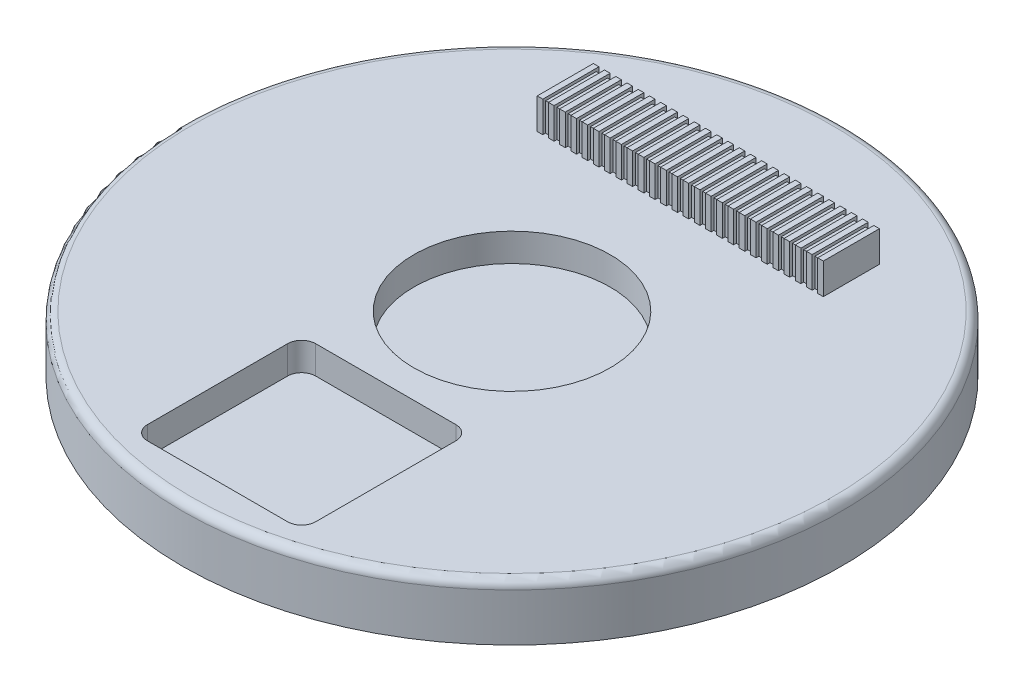
SolidWorks part; units mm, degrees
ref_plane "Front Plane" through (0, 0, 0) normal (0, 0, 1) x (1, 0, 0)
ref_plane "Top Plane" through (0, 0, 0) normal (0, 1, 0) x (1, 0, 0)
ref_plane "Right Plane" through (0, 0, 0) normal (1, 0, 0) x (0, 0, -1)
sketch "Sketch1" plane through (0, 0, 0) normal (0, 1, 0) x (1, 0, 0)
  circle A0 centre (0, 0) radius 117.5
  dimension "D1" = 235
extrude "Boss-Extrude1" add sketch "Sketch1" along normal blind 20
sketch "Sketch2" plane through (0, 20, 0) normal (0, 1, 0) x (1, 0, 0)
  line L1 (-25, -105) -> (25, -105)
  line L2 (-30, -100) -> (-30, -50)
  line L3 (-25, -45) -> (25, -45)
  line L4 (30, -100) -> (30, -50)
  line L5 (0, -45) -> (0, -105) construction
  line L6 (-30, -75) -> (30, -75) construction
  circle A0 centre (0, 0) radius 35
  arc A1 (25, -105) -> (30, -100) centre (25, -100) ccw
  arc A2 (-25, -105) -> (-30, -100) centre (-25, -100) cw
  arc A3 (25, -45) -> (30, -50) centre (25, -50) cw
  arc A4 (-30, -50) -> (-25, -45) centre (-25, -50) cw
  point P3 (0, -75)
  point P7 (0, 0)
  point P13 (-30, -105)
  point P18 (-30, -45)
  point P19 (0, 0)
  point P20 (0, 0)
  dimension "D1" = 70
  dimension "D3" = 5
  dimension "D2" = 60
  dimension "D4" = 75
extrude "Cut-Extrude1" cut sketch "Sketch2" against normal blind 10
sketch "Sketch3" plane through (0, 20, 0) normal (0, 1, 0) x (1, 0, 0)
  line L1 (-51, 80) -> (51, 80)
  line L2 (-51, 80) -> (-51, 60)
  line L3 (-51, 60) -> (51, 60)
  line L4 (51, 80) -> (51, 60)
  line L5 (0, 60) -> (0, 80) construction
  line L6 (-51, 70) -> (51, 70) construction
  point P0 (0, 70)
  point P4 (0, 0)
  point P5 (0, 0)
  dimension "D1" = 70
  dimension "D2" = 20
  dimension "D3" = 102
extrude "Boss-Extrude2" add sketch "Sketch3" along normal blind 10
sketch "Sketch6" plane through (0, 30, 0) normal (0, 1, 0) x (1, 0, 0)
  line L0 (-51, 70) -> (51, 70) construction
  line L1 (-51, 80) -> (-51, 60) construction
  line L2 (51, 60) -> (51, 80) construction
  line L3 (51, 80) -> (-51, 80) construction
  line L4 (-51, 60) -> (-49, 60)
  line L5 (-51, 60) -> (-51, 80)
  line L6 (-51, 80) -> (-49, 80)
  line L7 (-49, 60) -> (-49, 80)
  line L8 (-50, 80) -> (-50, 60) construction
  line L9 (-51, 70) -> (-49, 70) construction
  line L10 (-45, 60) -> (-45, 80)
  line L11 (-47, 60) -> (-45, 60)
  line L12 (-47, 60) -> (-47, 80)
  line L13 (-47, 80) -> (-45, 80)
  line L14 (-41, 60) -> (-41, 80)
  line L15 (-43, 60) -> (-41, 60)
  line L16 (-43, 60) -> (-43, 80)
  line L17 (-43, 80) -> (-41, 80)
  line L18 (-37, 60) -> (-37, 80)
  line L19 (-39, 60) -> (-37, 60)
  line L20 (-39, 60) -> (-39, 80)
  line L21 (-39, 80) -> (-37, 80)
  line L22 (-33, 60) -> (-33, 80)
  line L23 (-35, 60) -> (-33, 60)
  line L24 (-35, 60) -> (-35, 80)
  line L25 (-35, 80) -> (-33, 80)
  line L26 (-29, 60) -> (-29, 80)
  line L27 (-31, 60) -> (-29, 60)
  line L28 (-31, 60) -> (-31, 80)
  line L29 (-31, 80) -> (-29, 80)
  line L30 (-25, 60) -> (-25, 80)
  line L31 (-27, 60) -> (-25, 60)
  line L32 (-27, 60) -> (-27, 80)
  line L33 (-27, 80) -> (-25, 80)
  line L34 (-21, 60) -> (-21, 80)
  line L35 (-23, 60) -> (-21, 60)
  line L36 (-23, 60) -> (-23, 80)
  line L37 (-23, 80) -> (-21, 80)
  line L38 (-17, 60) -> (-17, 80)
  line L39 (-19, 60) -> (-17, 60)
  line L40 (-19, 60) -> (-19, 80)
  line L41 (-19, 80) -> (-17, 80)
  line L42 (-13, 60) -> (-13, 80)
  line L43 (-15, 60) -> (-13, 60)
  line L44 (-15, 60) -> (-15, 80)
  line L45 (-15, 80) -> (-13, 80)
  line L46 (-9, 60) -> (-9, 80)
  line L47 (-11, 60) -> (-9, 60)
  line L48 (-11, 60) -> (-11, 80)
  line L49 (-11, 80) -> (-9, 80)
  line L50 (-5, 60) -> (-5, 80)
  line L51 (-7, 60) -> (-5, 60)
  line L52 (-7, 60) -> (-7, 80)
  line L53 (-7, 80) -> (-5, 80)
  line L54 (-1, 60) -> (-1, 80)
  line L55 (-3, 60) -> (-1, 60)
  line L56 (-3, 60) -> (-3, 80)
  line L57 (-3, 80) -> (-1, 80)
  line L58 (3, 60) -> (3, 80)
  line L59 (1, 60) -> (3, 60)
  line L60 (1, 60) -> (1, 80)
  line L61 (1, 80) -> (3, 80)
  line L62 (7, 60) -> (7, 80)
  line L63 (5, 60) -> (7, 60)
  line L64 (5, 60) -> (5, 80)
  line L65 (5, 80) -> (7, 80)
  line L66 (11, 60) -> (11, 80)
  line L67 (9, 60) -> (11, 60)
  line L68 (9, 60) -> (9, 80)
  line L69 (9, 80) -> (11, 80)
  line L70 (15, 60) -> (15, 80)
  line L71 (13, 60) -> (15, 60)
  line L72 (13, 60) -> (13, 80)
  line L73 (13, 80) -> (15, 80)
  line L74 (19, 60) -> (19, 80)
  line L75 (17, 60) -> (19, 60)
  line L76 (17, 60) -> (17, 80)
  line L77 (17, 80) -> (19, 80)
  line L78 (23, 60) -> (23, 80)
  line L79 (21, 60) -> (23, 60)
  line L80 (21, 60) -> (21, 80)
  line L81 (21, 80) -> (23, 80)
  line L82 (27, 60) -> (27, 80)
  line L83 (25, 60) -> (27, 60)
  line L84 (25, 60) -> (25, 80)
  line L85 (25, 80) -> (27, 80)
  line L86 (31, 60) -> (31, 80)
  line L87 (29, 60) -> (31, 60)
  line L88 (29, 60) -> (29, 80)
  line L89 (29, 80) -> (31, 80)
  line L90 (35, 60) -> (35, 80)
  line L91 (33, 60) -> (35, 60)
  line L92 (33, 60) -> (33, 80)
  line L93 (33, 80) -> (35, 80)
  line L94 (39, 60) -> (39, 80)
  line L95 (37, 60) -> (39, 60)
  line L96 (37, 60) -> (37, 80)
  line L97 (37, 80) -> (39, 80)
  line L98 (43, 60) -> (43, 80)
  line L99 (41, 60) -> (43, 60)
  line L100 (41, 60) -> (41, 80)
  line L101 (41, 80) -> (43, 80)
  line L102 (47, 60) -> (47, 80)
  line L103 (45, 60) -> (47, 60)
  line L104 (45, 60) -> (45, 80)
  line L105 (45, 80) -> (47, 80)
  line L106 (51, 60) -> (51, 80)
  line L107 (49, 60) -> (51, 60)
  line L108 (49, 60) -> (49, 80)
  line L109 (49, 80) -> (51, 80)
  line L110 (-49, 60) -> (-45, 60) construction
  point P6 (-50, 70)
  point P12 (0, 0)
  point P16 (0, 0)
  point P116 (-46, 80)
  point P117 (0, 0)
  dimension "D1" = 2
  dimension "D3" = 4
  dimension "D2" = 26
extrude "Boss-Extrude3" add sketch "Sketch6" along normal blind 1
sketch "Sketch7" plane through (0, 0, -60) normal (0, 0, 1) x (1, 0, 0)
  line L0 (-51, 20) -> (51, 20) construction
  line L1 (-49, 30) -> (-47, 30)
  line L2 (-49, 30) -> (-49, 20)
  line L3 (-49, 20) -> (-47, 20)
  line L4 (-47, 30) -> (-47, 20)
  line L5 (-45, 30) -> (-45, 20)
  line L6 (-43, 30) -> (-43, 20)
  line L7 (-45, 30) -> (-43, 30)
  line L8 (-45, 20) -> (-43, 20)
  line L9 (-41, 30) -> (-41, 20)
  line L10 (-39, 30) -> (-39, 20)
  line L11 (-41, 30) -> (-39, 30)
  line L12 (-41, 20) -> (-39, 20)
  line L13 (-37, 30) -> (-37, 20)
  line L14 (-35, 30) -> (-35, 20)
  line L15 (-37, 30) -> (-35, 30)
  line L16 (-37, 20) -> (-35, 20)
  line L17 (-33, 30) -> (-33, 20)
  line L18 (-31, 30) -> (-31, 20)
  line L19 (-33, 30) -> (-31, 30)
  line L20 (-33, 20) -> (-31, 20)
  line L21 (-29, 30) -> (-29, 20)
  line L22 (-27, 30) -> (-27, 20)
  line L23 (-29, 30) -> (-27, 30)
  line L24 (-29, 20) -> (-27, 20)
  line L25 (-25, 30) -> (-25, 20)
  line L26 (-23, 30) -> (-23, 20)
  line L27 (-25, 30) -> (-23, 30)
  line L28 (-25, 20) -> (-23, 20)
  line L29 (-21, 30) -> (-21, 20)
  line L30 (-19, 30) -> (-19, 20)
  line L31 (-21, 30) -> (-19, 30)
  line L32 (-21, 20) -> (-19, 20)
  line L33 (-17, 30) -> (-17, 20)
  line L34 (-15, 30) -> (-15, 20)
  line L35 (-17, 30) -> (-15, 30)
  line L36 (-17, 20) -> (-15, 20)
  line L37 (-13, 30) -> (-13, 20)
  line L38 (-11, 30) -> (-11, 20)
  line L39 (-13, 30) -> (-11, 30)
  line L40 (-13, 20) -> (-11, 20)
  line L41 (-9, 30) -> (-9, 20)
  line L42 (-7, 30) -> (-7, 20)
  line L43 (-9, 30) -> (-7, 30)
  line L44 (-9, 20) -> (-7, 20)
  line L45 (-5, 30) -> (-5, 20)
  line L46 (-3, 30) -> (-3, 20)
  line L47 (-5, 30) -> (-3, 30)
  line L48 (-5, 20) -> (-3, 20)
  line L49 (-1, 30) -> (-1, 20)
  line L50 (1, 30) -> (1, 20)
  line L51 (-1, 30) -> (1, 30)
  line L52 (-1, 20) -> (1, 20)
  line L53 (3, 30) -> (3, 20)
  line L54 (5, 30) -> (5, 20)
  line L55 (3, 30) -> (5, 30)
  line L56 (3, 20) -> (5, 20)
  line L57 (7, 30) -> (7, 20)
  line L58 (9, 30) -> (9, 20)
  line L59 (7, 30) -> (9, 30)
  line L60 (7, 20) -> (9, 20)
  line L61 (11, 30) -> (11, 20)
  line L62 (13, 30) -> (13, 20)
  line L63 (11, 30) -> (13, 30)
  line L64 (11, 20) -> (13, 20)
  line L65 (15, 30) -> (15, 20)
  line L66 (17, 30) -> (17, 20)
  line L67 (15, 30) -> (17, 30)
  line L68 (15, 20) -> (17, 20)
  line L69 (19, 30) -> (19, 20)
  line L70 (21, 30) -> (21, 20)
  line L71 (19, 30) -> (21, 30)
  line L72 (19, 20) -> (21, 20)
  line L73 (23, 30) -> (23, 20)
  line L74 (25, 30) -> (25, 20)
  line L75 (23, 30) -> (25, 30)
  line L76 (23, 20) -> (25, 20)
  line L77 (27, 30) -> (27, 20)
  line L78 (29, 30) -> (29, 20)
  line L79 (27, 30) -> (29, 30)
  line L80 (27, 20) -> (29, 20)
  line L81 (31, 30) -> (31, 20)
  line L82 (33, 30) -> (33, 20)
  line L83 (31, 30) -> (33, 30)
  line L84 (31, 20) -> (33, 20)
  line L85 (35, 30) -> (35, 20)
  line L86 (37, 30) -> (37, 20)
  line L87 (35, 30) -> (37, 30)
  line L88 (35, 20) -> (37, 20)
  line L89 (39, 30) -> (39, 20)
  line L90 (41, 30) -> (41, 20)
  line L91 (39, 30) -> (41, 30)
  line L92 (39, 20) -> (41, 20)
  line L93 (43, 30) -> (43, 20)
  line L94 (45, 30) -> (45, 20)
  line L95 (43, 30) -> (45, 30)
  line L96 (43, 20) -> (45, 20)
  line L97 (47, 30) -> (47, 20)
  line L98 (49, 30) -> (49, 20)
  line L99 (47, 30) -> (49, 30)
  line L100 (47, 20) -> (49, 20)
  line L101 (-49, 30) -> (-45, 30) construction
  point P7 (0, 0)
  point P9 (0, 0)
  point P107 (0, 0)
  point P108 (0, 0)
  point P109 (0, 0)
  point P110 (0, 0)
  point P111 (0, 0)
  point P112 (0, 0)
  point P113 (0, 0)
  point P114 (0, 0)
  point P115 (0, 0)
  point P116 (0, 0)
  point P117 (0, 0)
  point P118 (0, 0)
  point P119 (0, 0)
  point P120 (0, 0)
  point P121 (0, 0)
  point P122 (0, 0)
  point P123 (0, 0)
  point P124 (0, 0)
  point P125 (0, 0)
  point P126 (0, 0)
  dimension "D1" = 2
  dimension "D3" = 4
  dimension "D2" = 25
extrude "Cut-Extrude2" cut sketch "Sketch7" against normal blind 1
sketch "Sketch8" plane through (0, 0, -80) normal (0, 0, -1) x (-1, 0, 0)
  line L0 (117.5, 20) -> (-117.5, 20) construction
  line L1 (-49, 30) -> (-47, 30)
  line L2 (-49, 30) -> (-49, 20)
  line L3 (-49, 20) -> (-47, 20)
  line L4 (-47, 30) -> (-47, 20)
  line L5 (-45, 30) -> (-45, 20)
  line L6 (-45, 20) -> (-43, 20)
  line L7 (-43, 30) -> (-43, 20)
  line L8 (-45, 30) -> (-43, 30)
  line L9 (-41, 30) -> (-41, 20)
  line L10 (-41, 20) -> (-39, 20)
  line L11 (-39, 30) -> (-39, 20)
  line L12 (-41, 30) -> (-39, 30)
  line L13 (-37, 30) -> (-37, 20)
  line L14 (-37, 20) -> (-35, 20)
  line L15 (-35, 30) -> (-35, 20)
  line L16 (-37, 30) -> (-35, 30)
  line L17 (-33, 30) -> (-33, 20)
  line L18 (-33, 20) -> (-31, 20)
  line L19 (-31, 30) -> (-31, 20)
  line L20 (-33, 30) -> (-31, 30)
  line L21 (-29, 30) -> (-29, 20)
  line L22 (-29, 20) -> (-27, 20)
  line L23 (-27, 30) -> (-27, 20)
  line L24 (-29, 30) -> (-27, 30)
  line L25 (-25, 30) -> (-25, 20)
  line L26 (-25, 20) -> (-23, 20)
  line L27 (-23, 30) -> (-23, 20)
  line L28 (-25, 30) -> (-23, 30)
  line L29 (-21, 30) -> (-21, 20)
  line L30 (-21, 20) -> (-19, 20)
  line L31 (-19, 30) -> (-19, 20)
  line L32 (-21, 30) -> (-19, 30)
  line L33 (-17, 30) -> (-17, 20)
  line L34 (-17, 20) -> (-15, 20)
  line L35 (-15, 30) -> (-15, 20)
  line L36 (-17, 30) -> (-15, 30)
  line L37 (-13, 30) -> (-13, 20)
  line L38 (-13, 20) -> (-11, 20)
  line L39 (-11, 30) -> (-11, 20)
  line L40 (-13, 30) -> (-11, 30)
  line L41 (-9, 30) -> (-9, 20)
  line L42 (-9, 20) -> (-7, 20)
  line L43 (-7, 30) -> (-7, 20)
  line L44 (-9, 30) -> (-7, 30)
  line L45 (-5, 30) -> (-5, 20)
  line L46 (-5, 20) -> (-3, 20)
  line L47 (-3, 30) -> (-3, 20)
  line L48 (-5, 30) -> (-3, 30)
  line L49 (-1, 30) -> (-1, 20)
  line L50 (-1, 20) -> (1, 20)
  line L51 (1, 30) -> (1, 20)
  line L52 (-1, 30) -> (1, 30)
  line L53 (3, 30) -> (3, 20)
  line L54 (3, 20) -> (5, 20)
  line L55 (5, 30) -> (5, 20)
  line L56 (3, 30) -> (5, 30)
  line L57 (7, 30) -> (7, 20)
  line L58 (7, 20) -> (9, 20)
  line L59 (9, 30) -> (9, 20)
  line L60 (7, 30) -> (9, 30)
  line L61 (11, 30) -> (11, 20)
  line L62 (11, 20) -> (13, 20)
  line L63 (13, 30) -> (13, 20)
  line L64 (11, 30) -> (13, 30)
  line L65 (15, 30) -> (15, 20)
  line L66 (15, 20) -> (17, 20)
  line L67 (17, 30) -> (17, 20)
  line L68 (15, 30) -> (17, 30)
  line L69 (19, 30) -> (19, 20)
  line L70 (19, 20) -> (21, 20)
  line L71 (21, 30) -> (21, 20)
  line L72 (19, 30) -> (21, 30)
  line L73 (23, 30) -> (23, 20)
  line L74 (23, 20) -> (25, 20)
  line L75 (25, 30) -> (25, 20)
  line L76 (23, 30) -> (25, 30)
  line L77 (27, 30) -> (27, 20)
  line L78 (27, 20) -> (29, 20)
  line L79 (29, 30) -> (29, 20)
  line L80 (27, 30) -> (29, 30)
  line L81 (31, 30) -> (31, 20)
  line L82 (31, 20) -> (33, 20)
  line L83 (33, 30) -> (33, 20)
  line L84 (31, 30) -> (33, 30)
  line L85 (35, 30) -> (35, 20)
  line L86 (35, 20) -> (37, 20)
  line L87 (37, 30) -> (37, 20)
  line L88 (35, 30) -> (37, 30)
  line L89 (39, 30) -> (39, 20)
  line L90 (39, 20) -> (41, 20)
  line L91 (41, 30) -> (41, 20)
  line L92 (39, 30) -> (41, 30)
  line L93 (43, 30) -> (43, 20)
  line L94 (43, 20) -> (45, 20)
  line L95 (45, 30) -> (45, 20)
  line L96 (43, 30) -> (45, 30)
  line L97 (47, 30) -> (47, 20)
  line L98 (47, 20) -> (49, 20)
  line L99 (49, 30) -> (49, 20)
  line L100 (47, 30) -> (49, 30)
  line L101 (-49, 30) -> (-45, 30) construction
  point P7 (0, 0)
  point P8 (0, 0)
  dimension "D1" = 2
  dimension "D3" = 4
  dimension "D2" = 25
extrude "Cut-Extrude3" cut sketch "Sketch8" against normal blind 1
fillet "Fillet3" radius 3 1 edges at (0, 20, 117.5)
